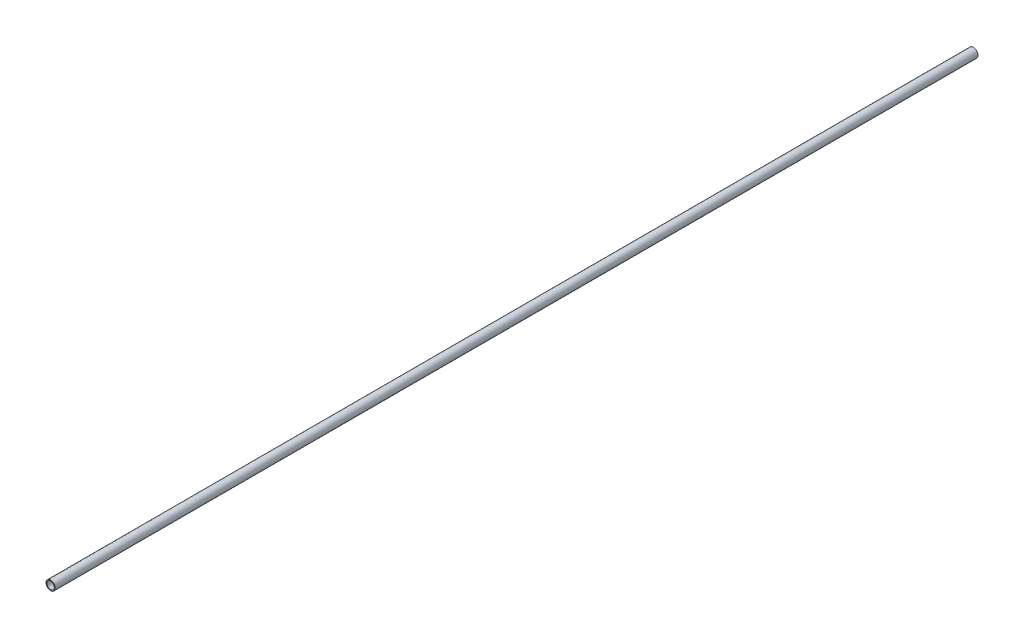
SolidWorks part; units mm, degrees
material "carbon fiber"
ref_plane "Front Plane" through (0, 0, 0) normal (0, 0, 1) x (1, 0, 0)
ref_plane "Top Plane" through (0, 0, 0) normal (0, 1, 0) x (1, 0, 0)
ref_plane "Right Plane" through (0, 0, 0) normal (1, 0, 0) x (0, 0, -1)
sketch "Эскиз1" plane through (0, 0, 0) normal (0, 0, 1) x (1, 0, 0)
  circle A0 centre (0, 0) radius 4
  circle A1 centre (0, 0) radius 5
  dimension "D1" = 1
  dimension "D2" = 8
extrude "Бобышка-Вытянуть1" add sketch "Эскиз1" along normal mid plane 1000
